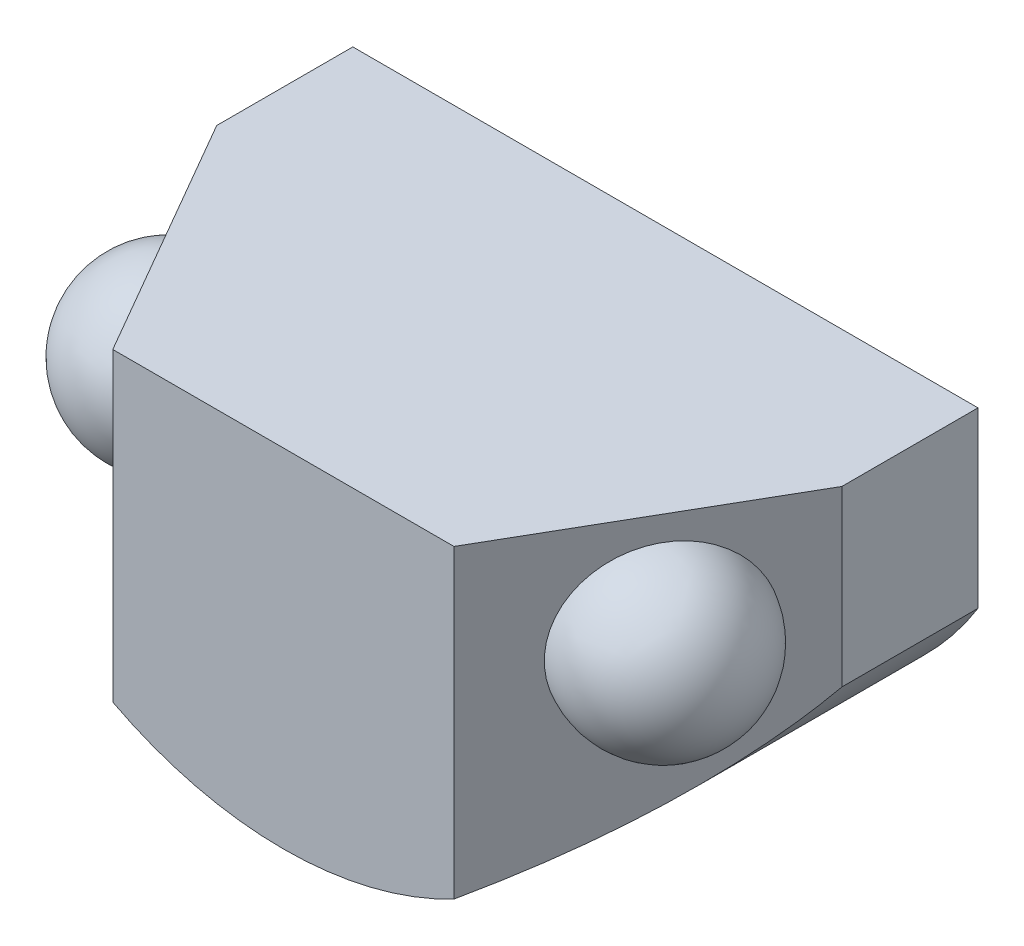
SolidWorks part; units mm, degrees
ref_plane "Front Plane" through (0, 0, 0) normal (0, 0, 1) x (1, 0, 0)
ref_plane "Top Plane" through (0, 0, 0) normal (0, 1, 0) x (1, 0, 0)
ref_plane "Right Plane" through (0, 0, 0) normal (1, 0, 0) x (0, 0, -1)
sketch "Sketch1" plane through (0, 0, 0) normal (0, 1, 0) x (1, 0, 0)
  line L1 (-90, -55) -> (90, -55)
  line L2 (-90, -55) -> (-90, 55)
  line L3 (-90, 55) -> (90, 55)
  line L4 (90, -55) -> (90, 55)
  line L5 (-90, -55) -> (90, 55) construction
  line L6 (-90, 55) -> (90, -55) construction
  point P0 (0, 0)
  dimension "D1" = 110
  dimension "D2" = 180
extrude "Boss-Extrude1" add sketch "Sketch1" along normal blind 50
sketch "Sketch2" plane through (-35, 0, -55) normal (0, 0, 1) x (1, 0, 0)
  line L2 (-55, 0) -> (125, 0) construction
  line L3 (-55, 0) -> (125, 0)
  arc A1 (-55, 0) -> (125, 0) centre (35, 56) ccw
  point P3 (35, -50)
  dimension "D1" = 50
extrude "Boss-Extrude2" add sketch "Sketch2" along normal up to surface (110 mm away) up to face at (0, 25, 55)
sketch "Sketch3" plane through (0, 50, 0) normal (0, 1, 0) x (1, 0, 0)
  line L0 (-49.1188, -55) -> (-90, 15.8083)
  line L1 (-90, -55) -> (90, -55) construction
  line L2 (-90, 55) -> (-90, -55) construction
  line L3 (-90, 15.8083) -> (-90, -55)
  line L4 (-90, -55) -> (-49.1188, -55)
  dimension "D1" = 30
extrude "Cut-Extrude1" cut sketch "Sketch3" against normal through all
mirror "Mirror1" about plane through (0, 0, 0) normal (1, 0, 0) of "Cut-Extrude1"
sketch "Sketch4" plane through (-60.6548, 0, 35.0191) normal (-0.866, 0, 0.5) x (0.5, 0, 0.866)
  line L0 (-20.9652, 42.9426) -> (-20.9652, -7.0574)
  arc A1 (-20.9652, 42.9426) -> (-20.9652, -7.0574) centre (-20.9652, 17.9426) cw
  dimension "D1" = 50
sketch "Sketch5" plane through (0, 0, -55) normal (0, 0, -1) x (-1, 0, 0)
  circle A0 centre (0, 0) radius 5
  dimension "D1" = 0
extrude "Boss-Extrude5" add sketch "Sketch5" along normal blind 10 and the other way blind 10
revolve "Revolve1" add sketch "Sketch4" angle 360 about L0
mirror "Mirror2" about plane through (0, 0, 0) normal (1, 0, 0) of "Revolve1"
